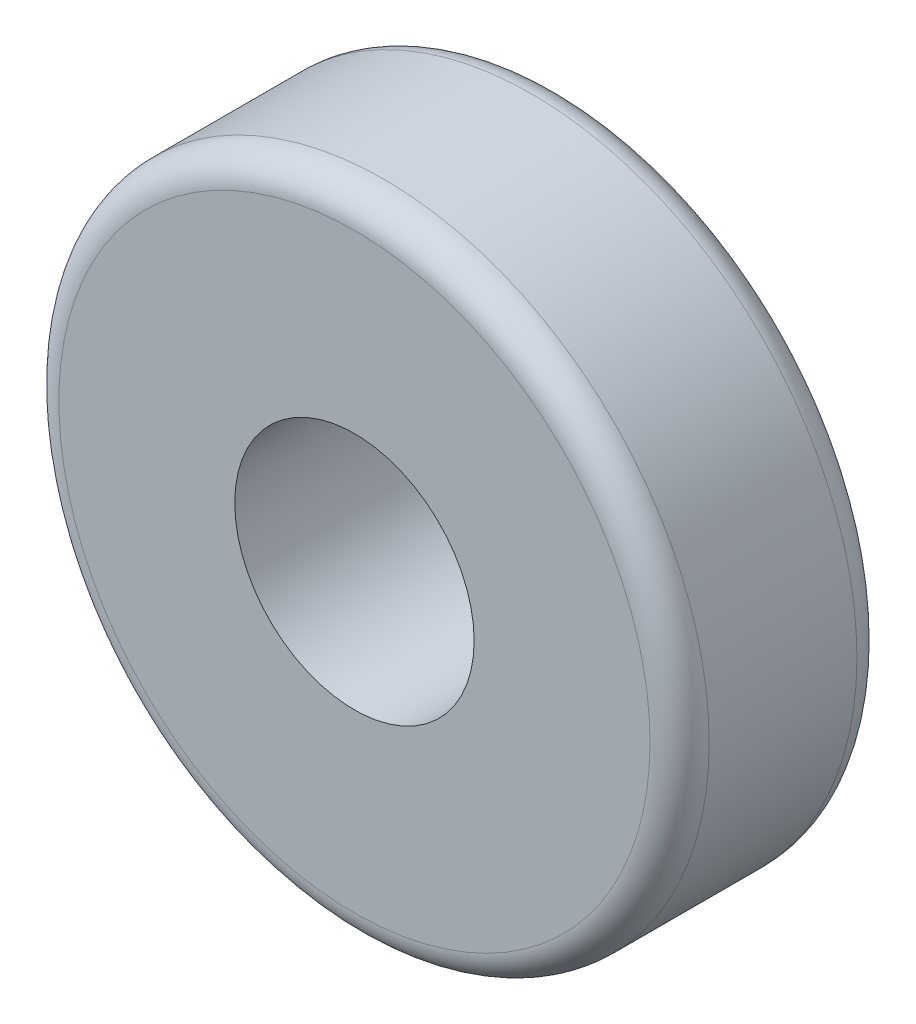
SolidWorks part; units mm, degrees
ref_plane "Alzado" through (0, 0, 0) normal (0, 0, 1) x (1, 0, 0)
ref_plane "Planta" through (0, 0, 0) normal (0, 1, 0) x (1, 0, 0)
ref_plane "Vista lateral" through (0, 0, 0) normal (1, 0, 0) x (0, 0, -1)
sketch "Croquis1" plane through (0, 0, 0) normal (0, 0, 1) x (1, 0, 0)
  circle A0 centre (0, 0) radius 4.05
  circle A1 centre (0, 0) radius 11
  dimension "D1" = 8.1
  dimension "D2" = 22
extrude "Saliente-Extruir1" add sketch "Croquis1" along normal blind 7
fillet "Redondeo1" radius 1 2 edges at (11, 0, 0) (11, 0, 7)
